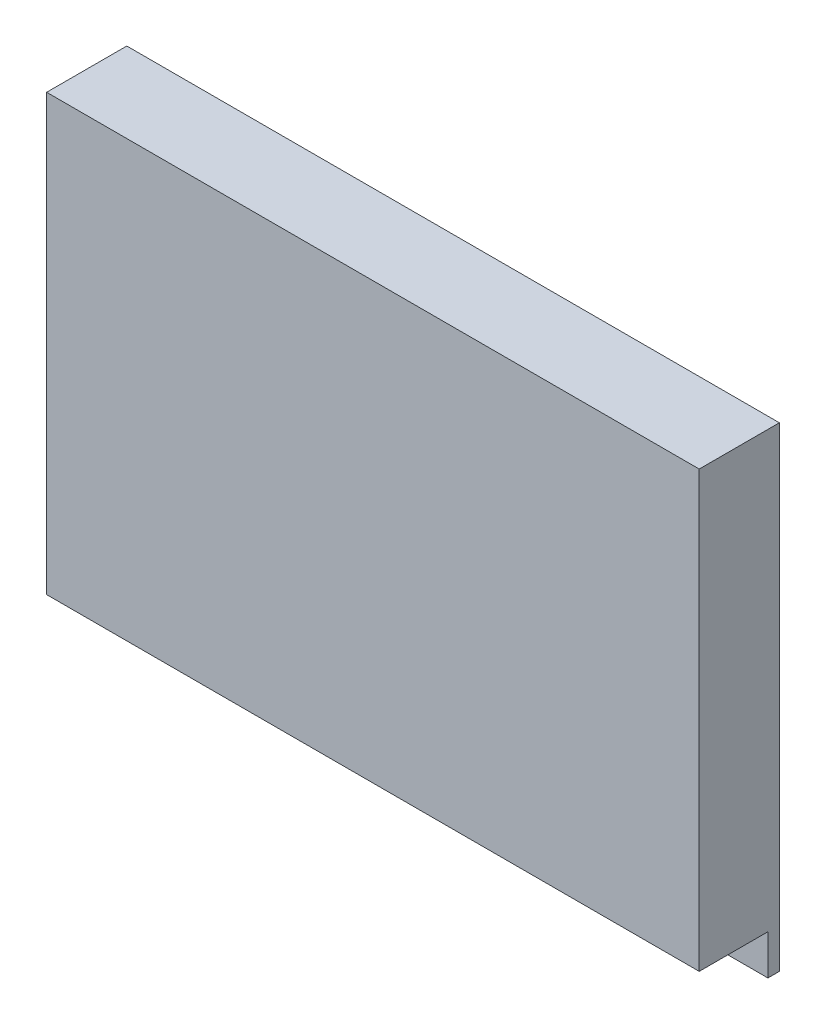
SolidWorks part; units mm, degrees
ref_plane "Front Plane" through (0, 0, 0) normal (0, 0, 1) x (1, 0, 0)
ref_plane "Top Plane" through (0, 0, 0) normal (0, 1, 0) x (1, 0, 0)
ref_plane "Right Plane" through (0, 0, 0) normal (1, 0, 0) x (0, 0, -1)
sketch "Sketch1" plane through (0, 0, 0) normal (0, 0, 1) x (1, 0, 0)
  line L1 (0, 0) -> (57, 0)
  line L2 (0, 0) -> (0, 41.5)
  line L3 (0, 41.5) -> (57, 41.5)
  line L4 (57, 0) -> (57, 41.5)
  dimension "D1" = 41.5
  dimension "D2" = 57
extrude "Boss-Extrude1" add sketch "Sketch1" along normal blind 1
sketch "Sketch2" plane through (0, 0, 1) normal (0, 0, 1) x (1, 0, 0)
  line L1 (57, 0) -> (57, 41.5) construction
  line L4 (0, 0) -> (57, 0) construction
  line L6 (57, 3.5) -> (0, 3.5)
  line L7 (57, 3.5) -> (57, 41.5)
  line L8 (57, 41.5) -> (0, 41.5)
  line L9 (0, 3.5) -> (0, 41.5)
  point P0 (57, 3.5)
  dimension "D1" = 3.5
extrude "Boss-Extrude2" add sketch "Sketch2" along normal blind 6
hole_wizard "Ø1.0mm Dowel Hole1" positions "3DSketch1" profile "Sketch3" hole size "Ø1.0" standard "ANSI Metric" end condition up to next
sketch3d "3DSketch1"
  line L0 (0, 0, 1) -> (57, 0, 1) construction
  line L1 (0, 3.5, 1) -> (0, 0, 1) construction
  point P0 (10, 1.5, 1)
  dimension "D1" = 1.5
  dimension "D2" = 10
sketch "Sketch3" plane through (10, 1.5, 1) normal (1, 0, 0) x (0, -1, 0)
  line L0 (0, 0) -> (0, 1)
  line L1 (0, 1) -> (0.8, 1)
  line L2 (0.8, 1) -> (0.8, 0)
  line L5 (0.8, 0) -> (0, 0)
  line L11 (0, -6.35) -> (0, 107.95) construction
  dimension "Thru Hole Dia." = 1.6
  dimension "Thru Hole Depth" = 1
